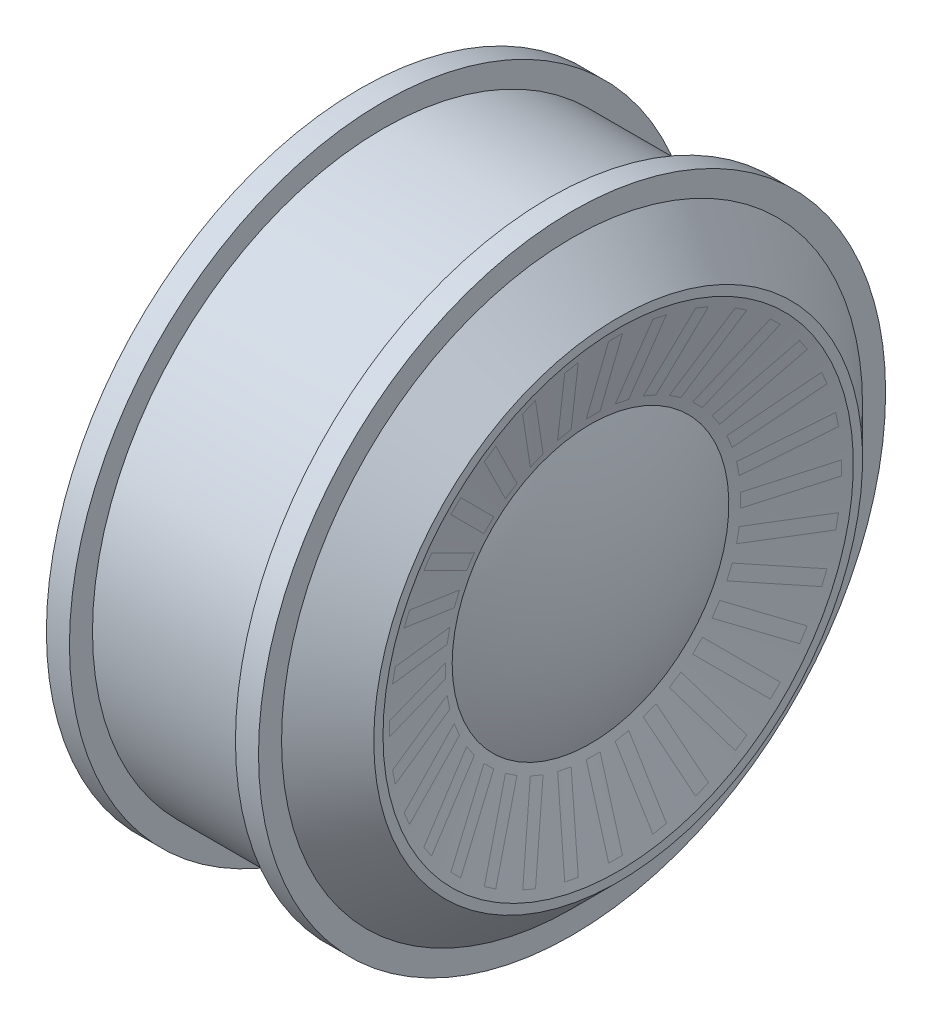
SolidWorks part; units mm, degrees
ref_plane "Front Plane" through (0, 0, 0) normal (0, 0, 1) x (1, 0, 0)
ref_plane "Top Plane" through (0, 0, 0) normal (0, 1, 0) x (1, 0, 0)
ref_plane "Right Plane" through (0, 0, 0) normal (1, 0, 0) x (0, 0, -1)
sketch "Croquis1" plane through (0, 0, 0) normal (0, 0, 1) x (1, 0, 0)
  line L0 (-754.8899, 0) -> (916.652, 0) construction
  line L1 (-23, 68) -> (-18, 68)
  line L2 (23, 68) -> (23, 63)
  line L3 (33, 0) -> (-23, 0)
  line L4 (-23, 0) -> (-23, 8)
  line L5 (0, 789.8385) -> (0, -518.2379) construction
  line L6 (-18, 68) -> (-18, 63)
  line L7 (-18, 63) -> (18, 63)
  line L8 (18, 63) -> (18, 68)
  line L9 (18, 68) -> (23, 68)
  line L10 (23, 63) -> (33, 53)
  line L12 (33, 53) -> (33, 51)
  line L13 (33, 51) -> (27, 30)
  line L14 (-23, 22.5) -> (-29, 16.5)
  line L15 (-29, 16.5) -> (-29, 8)
  line L16 (-29, 8) -> (-23, 8)
  line L17 (-23, 22.5) -> (-23, 68)
  arc A0 (27, 30) -> (33, 0) centre (-45, 0) cw
  dimension "D1" = 136
  dimension "D2" = 46
  dimension "D3" = 5
  dimension "D4" = 5
  dimension "D5" = 5
  dimension "D6" = 45
  dimension "D7" = 10
  dimension "D8" = 6
  dimension "D9" = 60
  dimension "D10" = 2
  dimension "D11" = 16
  dimension "D12" = 45
  dimension "D13" = 6
  dimension "D14" = 45
revolve "Revolución1" add sketch "Croquis1" angle 360 about L0
sketch "Croquis2" plane through (33, 0, 0) normal (1, 0, 0) x (0, 0, -1)
  line L0 (0, -83.0382) -> (0, 20.3706) construction
  line L1 (-1.5, 49) -> (1.5, 49)
  line L2 (-1.5, 49) -> (-1.5, 32)
  line L3 (-1.5, 32) -> (1.5, 32)
  line L4 (1.5, 49) -> (1.5, 32)
  line L5 (0, 51) -> (0, 49) construction
  line L6 (0, 30) -> (0, 32) construction
  line L7 (4.7717, 31.6778) -> (7.7141, 31.0925)
  line L8 (8.0882, 48.3511) -> (4.7717, 31.6778)
  line L9 (8.0882, 48.3511) -> (11.0306, 47.7658)
  line L10 (11.0306, 47.7658) -> (7.7141, 31.0925)
  line L11 (10.8601, 30.1382) -> (13.6317, 28.9901)
  line L12 (17.3657, 45.8441) -> (10.8601, 30.1382)
  line L13 (17.3657, 45.8441) -> (20.1373, 44.6961)
  line L14 (20.1373, 44.6961) -> (13.6317, 28.9901)
  line L15 (16.531, 27.4404) -> (19.0255, 25.7737)
  line L16 (25.9757, 41.5754) -> (16.531, 27.4404)
  line L17 (25.9757, 41.5754) -> (28.4701, 39.9087)
  line L18 (28.4701, 39.9087) -> (19.0255, 25.7737)
  line L19 (21.5668, 23.6881) -> (23.6881, 21.5668)
  line L20 (33.5876, 35.7089) -> (21.5668, 23.6881)
  line L21 (33.5876, 35.7089) -> (35.7089, 33.5876)
  line L22 (35.7089, 33.5876) -> (23.6881, 21.5668)
  line L23 (25.7737, 19.0255) -> (27.4404, 16.531)
  line L24 (39.9087, 28.4701) -> (25.7737, 19.0255)
  line L25 (39.9087, 28.4701) -> (41.5754, 25.9757)
  line L26 (41.5754, 25.9757) -> (27.4404, 16.531)
  line L27 (28.9901, 13.6317) -> (30.1382, 10.8601)
  line L28 (44.6961, 20.1373) -> (28.9901, 13.6317)
  line L29 (44.6961, 20.1373) -> (45.8441, 17.3657)
  line L30 (45.8441, 17.3657) -> (30.1382, 10.8601)
  line L31 (31.0925, 7.7141) -> (31.6778, 4.7717)
  line L32 (47.7658, 11.0306) -> (31.0925, 7.7141)
  line L33 (47.7658, 11.0306) -> (48.3511, 8.0882)
  line L34 (48.3511, 8.0882) -> (31.6778, 4.7717)
  line L35 (32, 1.5) -> (32, -1.5)
  line L36 (49, 1.5) -> (32, 1.5)
  line L37 (49, 1.5) -> (49, -1.5)
  line L38 (49, -1.5) -> (32, -1.5)
  line L39 (31.6778, -4.7717) -> (31.0925, -7.7141)
  line L40 (48.3511, -8.0882) -> (31.6778, -4.7717)
  line L41 (48.3511, -8.0882) -> (47.7658, -11.0306)
  line L42 (47.7658, -11.0306) -> (31.0925, -7.7141)
  line L43 (30.1382, -10.8601) -> (28.9901, -13.6317)
  line L44 (45.8441, -17.3657) -> (30.1382, -10.8601)
  line L45 (45.8441, -17.3657) -> (44.6961, -20.1373)
  line L46 (44.6961, -20.1373) -> (28.9901, -13.6317)
  line L47 (27.4404, -16.531) -> (25.7737, -19.0255)
  line L48 (41.5754, -25.9757) -> (27.4404, -16.531)
  line L49 (41.5754, -25.9757) -> (39.9087, -28.4701)
  line L50 (39.9087, -28.4701) -> (25.7737, -19.0255)
  line L51 (23.6881, -21.5668) -> (21.5668, -23.6881)
  line L52 (35.7089, -33.5876) -> (23.6881, -21.5668)
  line L53 (35.7089, -33.5876) -> (33.5876, -35.7089)
  line L54 (33.5876, -35.7089) -> (21.5668, -23.6881)
  line L55 (19.0255, -25.7737) -> (16.531, -27.4404)
  line L56 (28.4701, -39.9087) -> (19.0255, -25.7737)
  line L57 (28.4701, -39.9087) -> (25.9757, -41.5754)
  line L58 (25.9757, -41.5754) -> (16.531, -27.4404)
  line L59 (13.6317, -28.9901) -> (10.8601, -30.1382)
  line L60 (20.1373, -44.6961) -> (13.6317, -28.9901)
  line L61 (20.1373, -44.6961) -> (17.3657, -45.8441)
  line L62 (17.3657, -45.8441) -> (10.8601, -30.1382)
  line L63 (7.7141, -31.0925) -> (4.7717, -31.6778)
  line L64 (11.0306, -47.7658) -> (7.7141, -31.0925)
  line L65 (11.0306, -47.7658) -> (8.0882, -48.3511)
  line L66 (8.0882, -48.3511) -> (4.7717, -31.6778)
  line L67 (1.5, -32) -> (-1.5, -32)
  line L68 (1.5, -49) -> (1.5, -32)
  line L69 (1.5, -49) -> (-1.5, -49)
  line L70 (-1.5, -49) -> (-1.5, -32)
  line L71 (-4.7717, -31.6778) -> (-7.7141, -31.0925)
  line L72 (-8.0882, -48.3511) -> (-4.7717, -31.6778)
  line L73 (-8.0882, -48.3511) -> (-11.0306, -47.7658)
  line L74 (-11.0306, -47.7658) -> (-7.7141, -31.0925)
  line L75 (-10.8601, -30.1382) -> (-13.6317, -28.9901)
  line L76 (-17.3657, -45.8441) -> (-10.8601, -30.1382)
  line L77 (-17.3657, -45.8441) -> (-20.1373, -44.6961)
  line L78 (-20.1373, -44.6961) -> (-13.6317, -28.9901)
  line L79 (-16.531, -27.4404) -> (-19.0255, -25.7737)
  line L80 (-25.9757, -41.5754) -> (-16.531, -27.4404)
  line L81 (-25.9757, -41.5754) -> (-28.4701, -39.9087)
  line L82 (-28.4701, -39.9087) -> (-19.0255, -25.7737)
  line L83 (-21.5668, -23.6881) -> (-23.6881, -21.5668)
  line L84 (-33.5876, -35.7089) -> (-21.5668, -23.6881)
  line L85 (-33.5876, -35.7089) -> (-35.7089, -33.5876)
  line L86 (-35.7089, -33.5876) -> (-23.6881, -21.5668)
  line L87 (-25.7737, -19.0255) -> (-27.4404, -16.531)
  line L88 (-39.9087, -28.4701) -> (-25.7737, -19.0255)
  line L89 (-39.9087, -28.4701) -> (-41.5754, -25.9757)
  line L90 (-41.5754, -25.9757) -> (-27.4404, -16.531)
  line L91 (-28.9901, -13.6317) -> (-30.1382, -10.8601)
  line L92 (-44.6961, -20.1373) -> (-28.9901, -13.6317)
  line L93 (-44.6961, -20.1373) -> (-45.8441, -17.3657)
  line L94 (-45.8441, -17.3657) -> (-30.1382, -10.8601)
  line L95 (-31.0925, -7.7141) -> (-31.6778, -4.7717)
  line L96 (-47.7658, -11.0306) -> (-31.0925, -7.7141)
  line L97 (-47.7658, -11.0306) -> (-48.3511, -8.0882)
  line L98 (-48.3511, -8.0882) -> (-31.6778, -4.7717)
  line L99 (-32, -1.5) -> (-32, 1.5)
  line L100 (-49, -1.5) -> (-32, -1.5)
  line L101 (-49, -1.5) -> (-49, 1.5)
  line L102 (-49, 1.5) -> (-32, 1.5)
  line L103 (-31.6778, 4.7717) -> (-31.0925, 7.7141)
  line L104 (-48.3511, 8.0882) -> (-31.6778, 4.7717)
  line L105 (-48.3511, 8.0882) -> (-47.7658, 11.0306)
  line L106 (-47.7658, 11.0306) -> (-31.0925, 7.7141)
  line L107 (-30.1382, 10.8601) -> (-28.9901, 13.6317)
  line L108 (-45.8441, 17.3657) -> (-30.1382, 10.8601)
  line L109 (-45.8441, 17.3657) -> (-44.6961, 20.1373)
  line L110 (-44.6961, 20.1373) -> (-28.9901, 13.6317)
  line L111 (-27.4404, 16.531) -> (-25.7737, 19.0255)
  line L112 (-41.5754, 25.9757) -> (-27.4404, 16.531)
  line L113 (-41.5754, 25.9757) -> (-39.9087, 28.4701)
  line L114 (-39.9087, 28.4701) -> (-25.7737, 19.0255)
  line L115 (-23.6881, 21.5668) -> (-21.5668, 23.6881)
  line L116 (-35.7089, 33.5876) -> (-23.6881, 21.5668)
  line L117 (-35.7089, 33.5876) -> (-33.5876, 35.7089)
  line L118 (-33.5876, 35.7089) -> (-21.5668, 23.6881)
  line L119 (-19.0255, 25.7737) -> (-16.531, 27.4404)
  line L120 (-28.4701, 39.9087) -> (-19.0255, 25.7737)
  line L121 (-28.4701, 39.9087) -> (-25.9757, 41.5754)
  line L122 (-25.9757, 41.5754) -> (-16.531, 27.4404)
  line L123 (-13.6317, 28.9901) -> (-10.8601, 30.1382)
  line L124 (-20.1373, 44.6961) -> (-13.6317, 28.9901)
  line L125 (-20.1373, 44.6961) -> (-17.3657, 45.8441)
  line L126 (-17.3657, 45.8441) -> (-10.8601, 30.1382)
  line L127 (-7.7141, 31.0925) -> (-4.7717, 31.6778)
  line L128 (-11.0306, 47.7658) -> (-7.7141, 31.0925)
  line L129 (-11.0306, 47.7658) -> (-8.0882, 48.3511)
  line L130 (-8.0882, 48.3511) -> (-4.7717, 31.6778)
  line L131 (0, 0) -> (1.5, 32) construction
  circle A0 centre (0, 0) radius 30 construction
  circle A2 centre (0, 0) radius 30 construction
  circle A5 centre (0, 0) radius 51 construction
  dimension "D1" = 3
  dimension "D2" = 17
  dimension "D3" = 32
split line "Línea de partición1"
sketch "Croquis3" plane through (0, 0, 0) normal (0, 0, 1) x (1, 0, 0)
  line L0 (-98.057, 0) -> (115.6026, 0) construction
  line L1 (18, 63) -> (18, 68) construction
  line L3 (-18, 68) -> (-18, 63) construction
  line L4 (-18, 63) -> (18, 63) construction
  line L5 (18, 63) -> (18, 68)
  line L6 (-18, 68) -> (-18, 63)
  line L7 (-18, 63) -> (18, 63)
  line L8 (18, 68) -> (23, 68) construction
  line L9 (-23, 68) -> (-18, 68) construction
  line L10 (18, 68) -> (23, 68)
  line L11 (-23, 68) -> (-18, 68)
  line L13 (-23, 80) -> (47.8487, 80) construction
  line L16 (-23, 68) -> (-23, 75)
  line L17 (23, 68) -> (23, 75)
  arc A0 (-23, 75) -> (23, 75) centre (0, 24.6) cw
  dimension "D1" = 80
  dimension "D2" = 7
revolve "Revolución2" [suppressed] add sketch "Croquis3" angle 360 about L0
